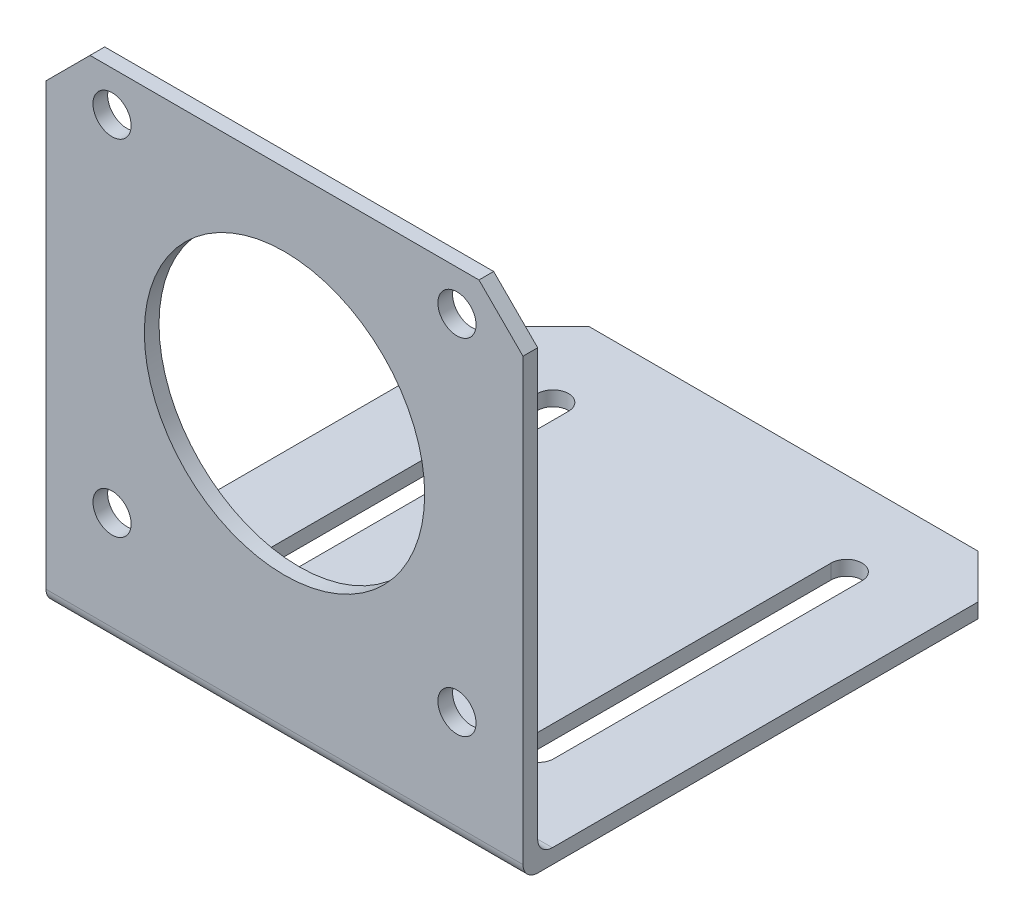
SolidWorks part; units mm, degrees
ref_plane "前视基准面" through (0, 0, 0) normal (0, 0, 1) x (1, 0, 0)
ref_plane "上视基准面" through (0, 0, 0) normal (0, 1, 0) x (1, 0, 0)
ref_plane "右视基准面" through (0, 0, 0) normal (1, 0, 0) x (0, 0, -1)
sketch "草图1" plane through (0, 0, 0) normal (0, 0, 1) x (1, 0, 0)
  line L1 (-28.9531, 50.5797) -> (36.0469, 50.5797)
  line L2 (-28.9531, 50.5797) -> (-28.9531, -17.4203)
  line L3 (-28.9531, -17.4203) -> (36.0469, -17.4203)
  line L4 (36.0469, 50.5797) -> (36.0469, -17.4203)
  circle A0 centre (3.5469, 21.5797) radius 19.1
  dimension "D3" = 38.2
  dimension "D4" = 39
  dimension "D1" = 68
  dimension "D2" = 65
extrude "凸台-拉伸1" add sketch "草图1" along normal blind 2
sketch "草图3" plane through (36.0469, 0, 0) normal (1, 0, 0) x (0, 0, -1)
  line L0 (0, -15.4203) -> (66, -15.4203)
  line L2 (66, -15.4203) -> (66, -17.4203)
  line L3 (66, -17.4203) -> (0, -17.4203)
  line L4 (-2, -17.4203) -> (-2, 50.5797) construction
  line L5 (0, -15.4203) -> (0, -17.4203)
  dimension "D1" = 68
extrude "凸台-拉伸2" add sketch "草图3" against normal blind 65
sketch "草图4" plane through (0, -15.4203, 0) normal (0, 1, 0) x (1, 0, 0)
  line L0 (3.5469, 0) -> (3.5469, 66) construction
  line L1 (-28.9531, 0) -> (36.0469, 0) construction
  line L2 (-28.9531, 66) -> (36.0469, 66) construction
  line L3 (23.5469, 12.5947) -> (23.5469, 54.5947) construction
  line L4 (21.4469, 12.5947) -> (21.4469, 54.5947)
  line L5 (25.6469, 12.5947) -> (25.6469, 54.5947)
  line L6 (36.0469, 66) -> (36.0469, 0) construction
  line L7 (-16.4531, 12.5947) -> (-16.4531, 54.5947) construction
  line L8 (-14.3531, 12.5947) -> (-14.3531, 54.5947)
  line L9 (-18.5531, 12.5947) -> (-18.5531, 54.5947)
  arc A0 (21.4469, 12.5947) -> (25.6469, 12.5947) centre (23.5469, 12.5947) ccw
  arc A1 (25.6469, 54.5947) -> (21.4469, 54.5947) centre (23.5469, 54.5947) ccw
  arc A2 (-14.3531, 12.5947) -> (-18.5531, 12.5947) centre (-16.4531, 12.5947) cw
  arc A3 (-18.5531, 54.5947) -> (-14.3531, 54.5947) centre (-16.4531, 54.5947) cw
  point P8 (23.5469, 33.5947)
  point P17 (-16.4531, 33.5947)
  dimension "D1" = 2.1
  dimension "D2" = 42
  dimension "D3" = 12.5
  dimension "D4" = 20
  dimension "D5" = 20
  dimension "D6" = 11.4053
extrude "切除-拉伸2" cut sketch "草图4" against normal through all contours L4 A1 L5 A0 | L9 A3 L8 A2
chamfer "倒角2" distance 6 angle 45 1 edges at (36.0469, -16.4203, -66)
chamfer "倒角3" distance 6 angle 45 1 edges at (-28.9531, -16.4203, -66)
chamfer "倒角4" distance 6 angle 45 1 edges at (-28.9531, 50.5797, 1)
chamfer "倒角5" distance 6 angle 45 1 edges at (36.0469, 50.5797, 1)
fillet "圆角1" radius 2 1 edges at (3.5469, -17.4203, 2)
fillet "圆角2" radius 2 1 edges at (3.5469, -15.4203, 0)
sketch "草图5" plane through (0, 0, 0) normal (0, 0, -1) x (-1, 0, 0)
  line L0 (-3.5469, 50.5797) -> (-3.5469, -49949.4203) construction
  line L1 (-30.0469, 50.5797) -> (22.9531, 50.5797) construction
  line L2 (-36.0469, -13.4203) -> (28.9531, -13.4203) construction
  line L3 (-22.6469, 21.5797) -> (15.5531, 21.5797) construction
  circle A0 centre (-27.0469, 45.0797) radius 2.6
  circle A1 centre (19.9531, 45.0797) radius 2.6
  circle A3 centre (19.9531, -1.9203) radius 2.6
  circle A4 centre (-27.0469, -1.9203) radius 2.6
  point P4 (-3.5469, 50.5797)
  point P7 (-3.5469, -13.4203)
  dimension "D1" = 5.2
  dimension "D2" = 23.5
  dimension "D3" = 47
extrude "切除-拉伸3" cut sketch "草图5" against normal through all
